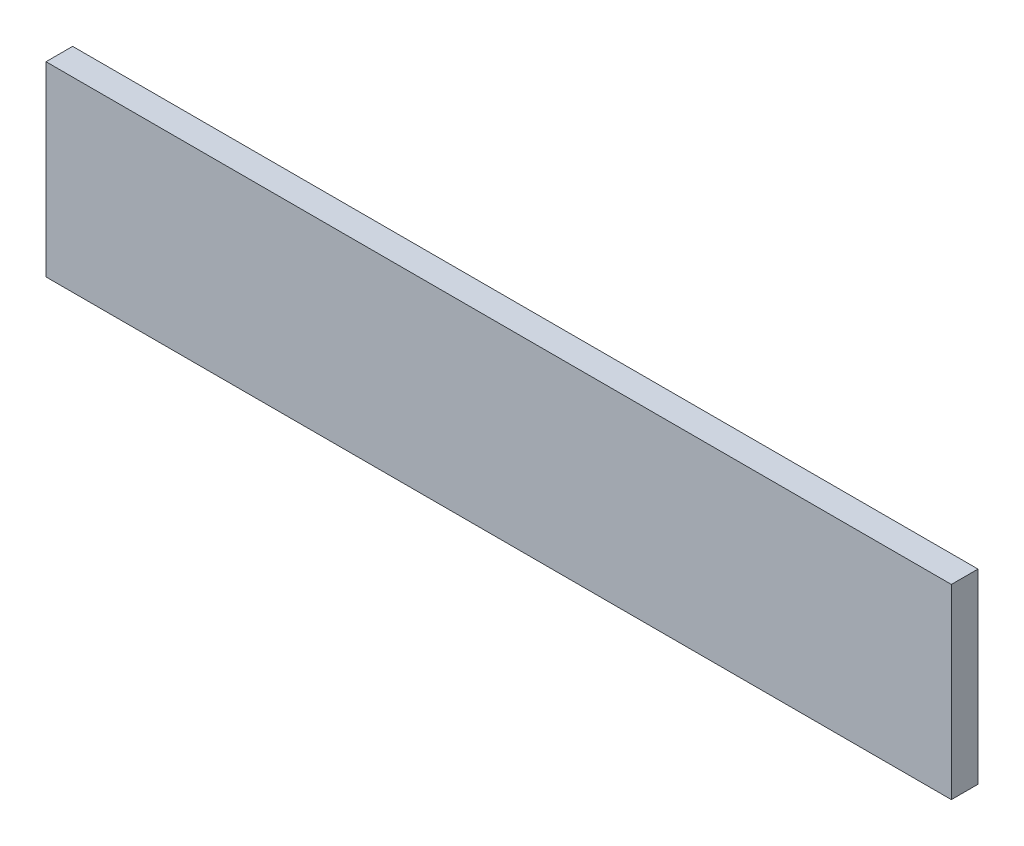
SolidWorks part; units mm, degrees
material "Plain Carbon Steel"
ref_plane "Front Plane" through (0, 0, 0) normal (0, 0, 1) x (1, 0, 0)
ref_plane "Top Plane" through (0, 0, 0) normal (0, 1, 0) x (1, 0, 0)
ref_plane "Right Plane" through (0, 0, 0) normal (1, 0, 0) x (0, 0, -1)
sketch "Sketch1" plane through (0, 0, 0) normal (0, 0, 1) x (1, 0, 0)
  line L0 (100, -37.7497) -> (100, 151.1829) construction
  line L1 (-70, 63) -> (270, 63)
  line L2 (-70, 63) -> (-70, -7)
  line L3 (-70, -7) -> (270, -7)
  line L4 (270, 63) -> (270, -7)
  line L5 (270, 28) -> (-70, 28) construction
  line L6 (100, 63) -> (100, -7) construction
  line L7 (-50, 2) -> (-50, 46) construction
  line L8 (-47, 63) -> (-10, 63) construction
  line L9 (247, -7) -> (-47, -7) construction
  point P4 (100, 63)
  point P17 (100, 28)
  dimension "D3" = 20
extrude "Boss-Extrude1" add sketch "Sketch1" along normal blind 10
